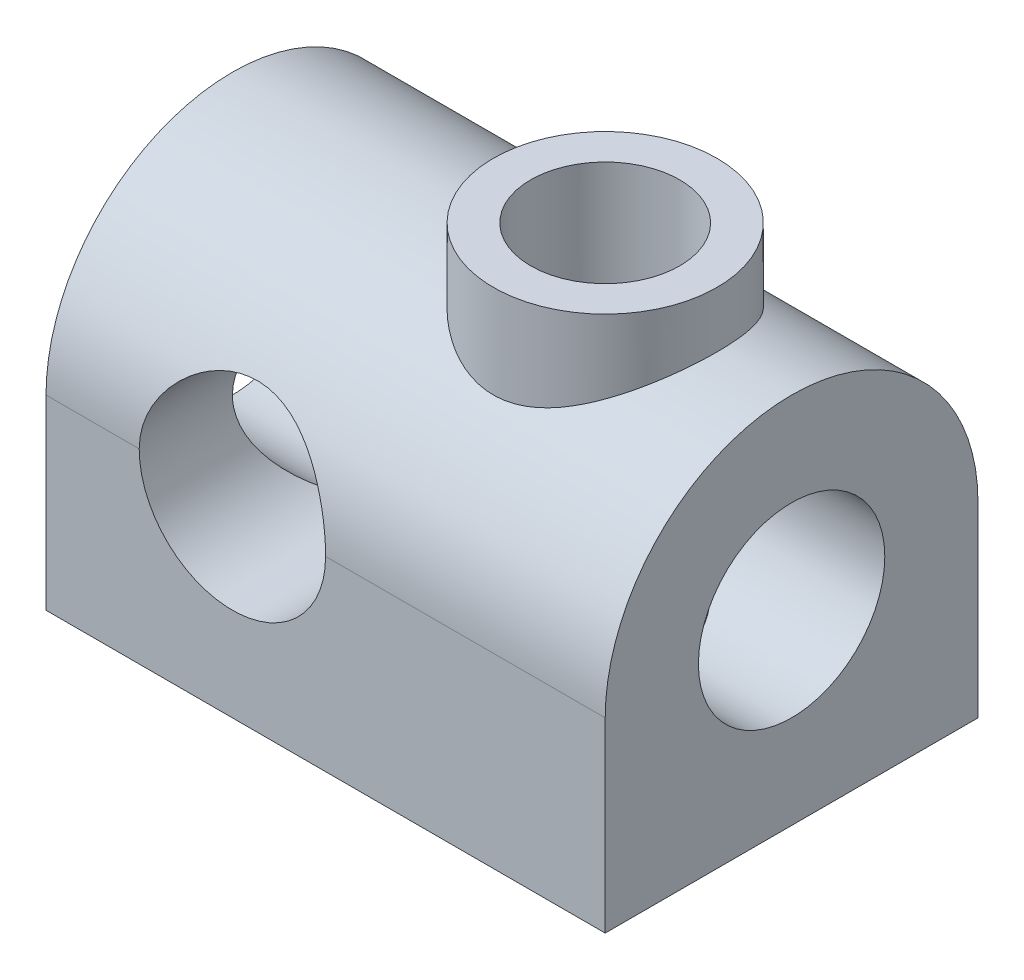
SolidWorks part; units mm, degrees
ref_plane "前视基准面" through (0, 0, 0) normal (0, 0, 1) x (1, 0, 0)
ref_plane "上视基准面" through (0, 0, 0) normal (0, 1, 0) x (1, 0, 0)
ref_plane "右视基准面" through (0, 0, 0) normal (1, 0, 0) x (0, 0, -1)
other "Configuration Table"
sketch "草图1" plane through (0, 0, 0) normal (1, 0, 0) x (0, 0, -1)
  line L0 (-20, 0) -> (-20, -20)
  line L1 (-20, -20) -> (20, -20)
  line L2 (20, -20) -> (20, 0)
  arc A0 (20, 0) -> (-20, 0) centre (0, 0) ccw
  point P4 (0, 0)
  point P7 (20, -20)
  dimension "D1" = 20
  dimension "D2" = 20
extrude "凸台-拉伸1" add sketch "草图1" along normal blind 60
sketch "草图3" plane through (0, -20, 0) normal (0, -1, 0) x (-1, 0, 0)
  line L0 (0, 0) -> (-40, 0) construction
  circle A0 centre (-40, 0) radius 12
  point P4 (0, 0)
  point P5 (0, 0)
  point P6 (0, 0)
  point P7 (-40, 0)
  point P8 (-39.7421, 0.4898)
  dimension "D1" = 24
  dimension "D2" = 40
extrude "凸台-拉伸2" add sketch "草图3" against normal blind 46 contours A0
sketch "草图6" plane through (0, 0, 0) normal (-1, 0, 0) x (0, 0, 1)
  circle A0 centre (0, 0) radius 10
  dimension "D1" = 20
extrude "切除-拉伸1" cut sketch "草图6" against normal through all
sketch "草图7" plane through (0, 26, 0) normal (0, 1, 0) x (1, 0, 0)
  line L0 (0, 0) -> (40, 0) construction
  circle A0 centre (40, 0) radius 8
  dimension "D1" = 16
  dimension "D2" = 40
extrude "切除-拉伸2" cut sketch "草图7" against normal through all contours A0
sketch "草图8" plane through (0, 0, 20) normal (0, 0, 1) x (1, 0, 0)
  line L0 (60, 0) -> (0, 0) construction
  line L1 (0, 0) -> (0, -20) construction
  circle A0 centre (20, 0) radius 10
  dimension "D1" = 20
  dimension "D2" = 20
extrude "切除-拉伸3" cut sketch "草图8" against normal through all
